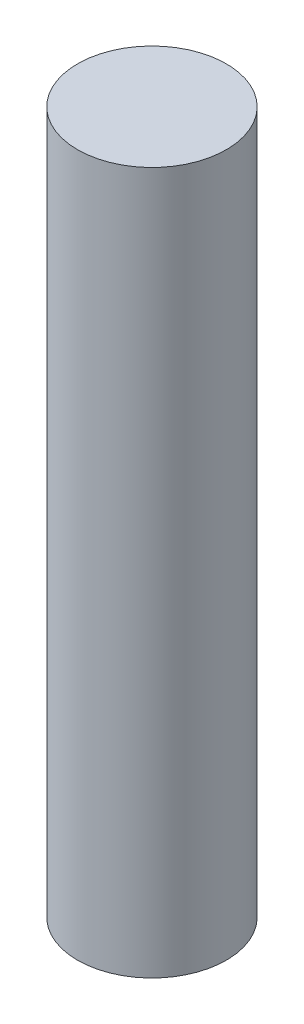
SolidWorks part; units mm, degrees
ref_plane "Front Plane" through (0, 0, 0) normal (0, 0, 1) x (1, 0, 0)
ref_plane "Top Plane" through (0, 0, 0) normal (0, 1, 0) x (1, 0, 0)
ref_plane "Right Plane" through (0, 0, 0) normal (1, 0, 0) x (0, 0, -1)
sketch "Sketch1" plane through (0, 0, 0) normal (0, 1, 0) x (1, 0, 0)
  circle A0 centre (-3.7316, 8.1888) radius 2.6924
  point P2 (0, 0)
  dimension "D1" = 5.3848
extrude "Boss-Extrude1" add sketch "Sketch1" along normal blind 25.4 contours A0
